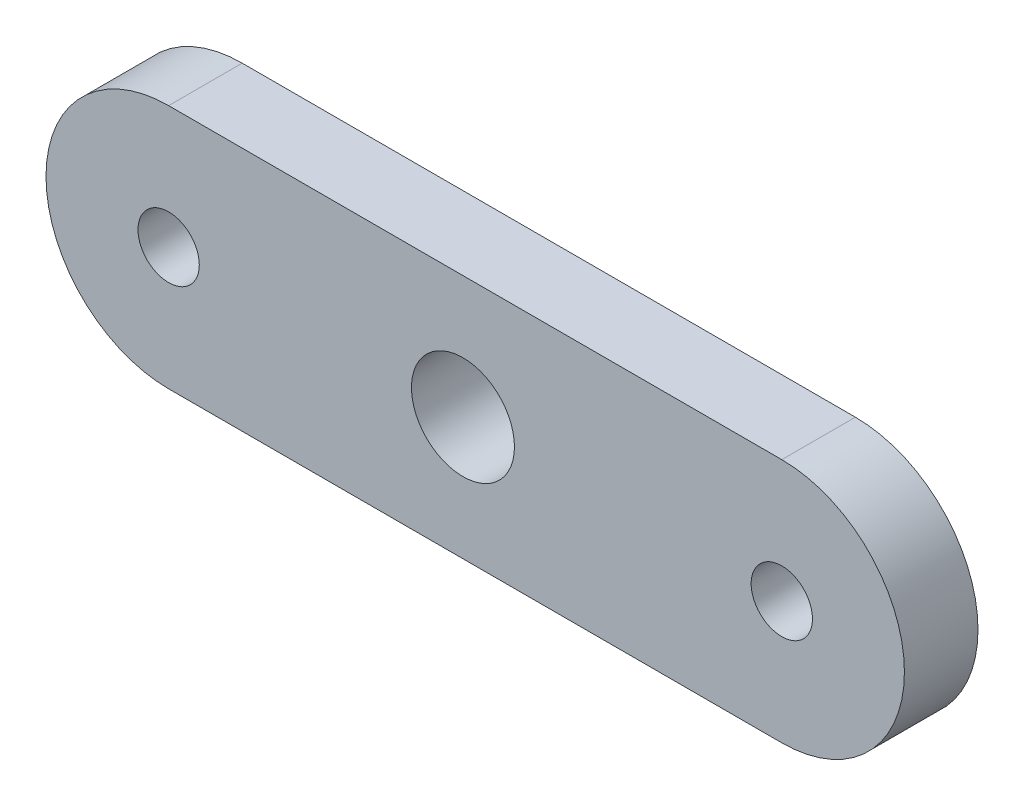
SolidWorks part; units mm, degrees
ref_plane "Front Plane" through (0, 0, 0) normal (0, 0, 1) x (1, 0, 0)
ref_plane "Top Plane" through (0, 0, 0) normal (0, 1, 0) x (1, 0, 0)
ref_plane "Right Plane" through (0, 0, 0) normal (1, 0, 0) x (0, 0, -1)
sketch "Sketch1" plane through (0, 0, 0) normal (0, 0, 1) x (1, 0, 0)
  line L0 (-78.0152, 31.0203) -> (-53.0152, 31.0203)
  line L2 (-53.0152, 21.0203) -> (-78.0152, 21.0203)
  arc A0 (-78.0152, 31.0203) -> (-78.0152, 21.0203) centre (-78.0152, 26.0203) ccw
  arc A1 (-53.0152, 21.0203) -> (-53.0152, 31.0203) centre (-53.0152, 26.0203) ccw
  circle A2 centre (-63.0152, 26.0203) radius 1.5
  circle A3 centre (-53.0152, 26.0203) radius 1.25
  circle A4 centre (-78.0152, 26.0203) radius 1.25
extrude "Boss-Extrude1" add sketch "Sketch1" along normal blind 3
sketch "Sketch5" plane through (0, 0, 3) normal (0, 0, 1) x (1, 0, 0)
  circle A0 centre (-66.0152, 26.0203) radius 2.1
extrude "Cut-Extrude2" cut sketch "Sketch5" against normal blind 10
sketch "Sketch6" plane through (0, 0, 3) normal (0, 0, 1) x (1, 0, 0)
  arc A0 (-64.1552, 25.0455) -> (-64.1552, 26.9952) centre (-63.0152, 26.0203) ccw
  arc A1 (-64.1552, 25.0455) -> (-64.1552, 26.9952) centre (-66.0152, 26.0203) ccw
extrude "Boss-Extrude2" add sketch "Sketch6" against normal blind 3
